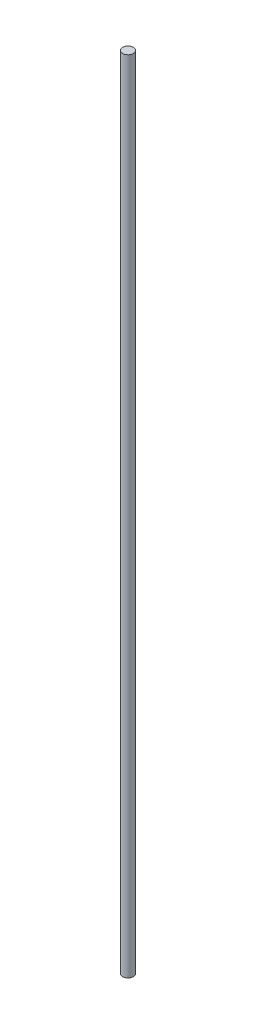
SolidWorks part; units mm, degrees
ref_plane "Front Plane" through (0, 0, 0) normal (0, 0, 1) x (1, 0, 0)
ref_plane "Top Plane" through (0, 0, 0) normal (0, 1, 0) x (1, 0, 0)
ref_plane "Right Plane" through (0, 0, 0) normal (1, 0, 0) x (0, 0, -1)
sketch "Sketch1" plane through (0, 0, 0) normal (0, 1, 0) x (1, 0, 0)
  circle A0 centre (0, 0) radius 4
  dimension "D1" = 8
extrude "Boss-Extrude1" add sketch "Sketch1" along normal blind 595
